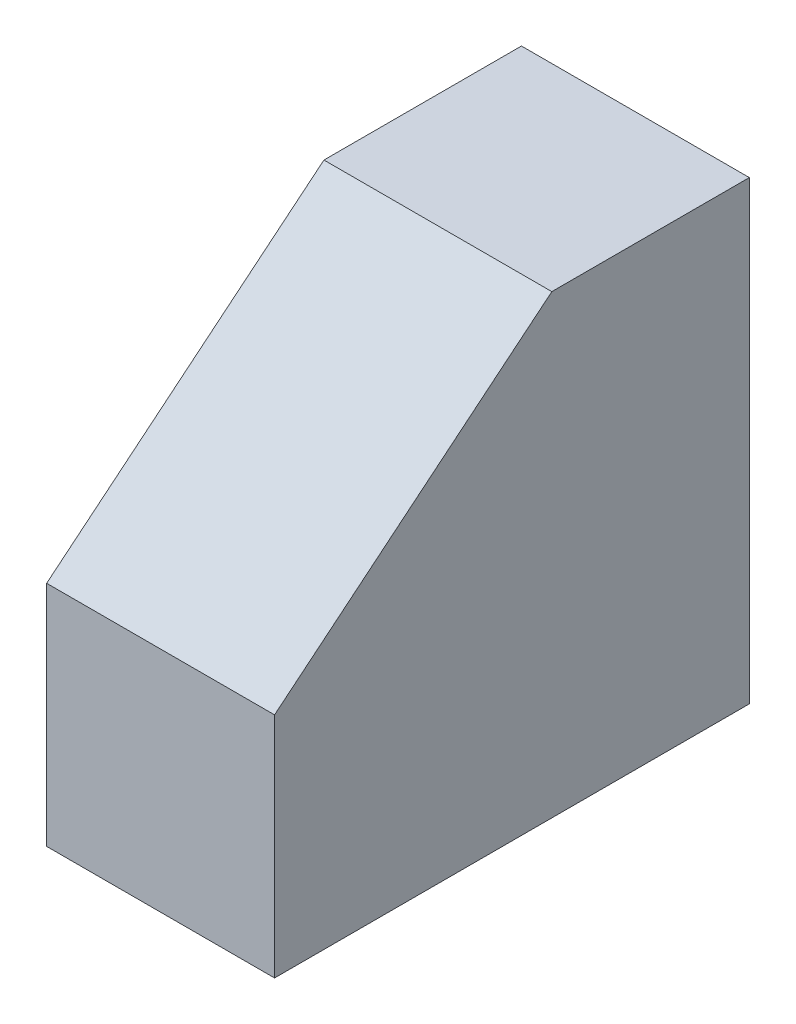
SolidWorks part; units mm, degrees
material "AISI 1010 钢，热轧条材"
ref_plane "前视基准面" through (0, 0, 0) normal (0, 0, 1) x (1, 0, 0)
ref_plane "上视基准面" through (0, 0, 0) normal (0, 1, 0) x (1, 0, 0)
ref_plane "右视基准面" through (0, 0, 0) normal (1, 0, 0) x (0, 0, -1)
other "Configuration Table"
sketch "草图1" plane through (0, 0, 0) normal (0, 1, 0) x (1, 0, 0)
  line L1 (0, 0) -> (300, 0)
  line L2 (0, 0) -> (0, 625)
  line L3 (0, 625) -> (300, 625)
  line L4 (300, 0) -> (300, 625)
  dimension "D1" = 300
  dimension "D2" = 625
extrude "凸台-拉伸1" add sketch "草图1" along normal blind 600
sketch "草图2" plane through (300, 0, 0) normal (1, 0, 0) x (0, 0, -1)
  line L0 (365, 600) -> (0, 600)
  line L1 (0, 600) -> (625, 600) construction
  line L2 (0, 600) -> (0, 300)
  line L3 (0, 600) -> (0, 0) construction
  line L4 (0, 300) -> (365, 600)
  dimension "D1" = 260
extrude "切除-拉伸1" cut sketch "草图2" against normal blind 600
